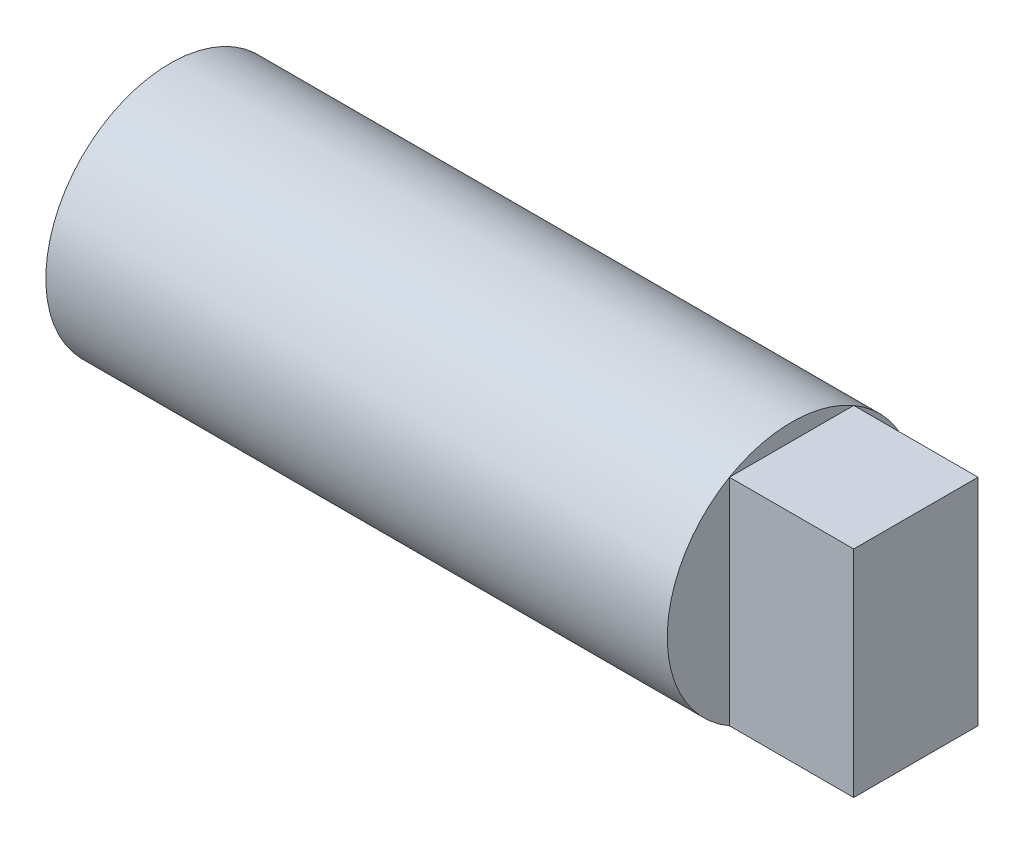
SolidWorks part; units mm, degrees
ref_plane "前视基准面" through (0, 0, 0) normal (0, 0, 1) x (1, 0, 0)
ref_plane "上视基准面" through (0, 0, 0) normal (0, 1, 0) x (1, 0, 0)
ref_plane "右视基准面" through (0, 0, 0) normal (1, 0, 0) x (0, 0, -1)
other "Configuration Table"
sketch "草图1" plane through (0, 0, 0) normal (1, 0, 0) x (0, 0, -1)
  circle A0 centre (0, 0) radius 30
extrude "凸台-拉伸1" add sketch "草图1" along normal blind 10 contours A0
sketch "草图2" plane through (10, 0, 0) normal (1, 0, 0) x (0, 0, -1)
  circle A0 centre (0, 0) radius 10
  circle A1 centre (0, 0) radius 30
extrude "切除-拉伸1" cut sketch "草图2" against normal blind 10
sketch "草图4" plane through (10, 0, 0) normal (1, 0, 0) x (0, 0, -1)
  circle A0 centre (0, 0) radius 10
extrude "凸台-拉伸2" add sketch "草图4" along normal blind 40
sketch "草图5" plane through (50, 0, 0) normal (1, 0, 0) x (0, 0, -1)
  line L1 (-5, -8.6603) -> (5, -8.6603)
  line L2 (-5, -8.6603) -> (-5, 8.6603)
  line L3 (-5, 8.6603) -> (5, 8.6603)
  line L4 (5, -8.6603) -> (5, 8.6603)
  line L5 (-5, -8.6603) -> (5, 8.6603) construction
  line L6 (-5, 8.6603) -> (5, -8.6603) construction
  circle A0 centre (0, 0) radius 10 construction
  point P0 (0, 0)
  dimension "D1" = 10
extrude "凸台-拉伸3" add sketch "草图5" along normal blind 10
